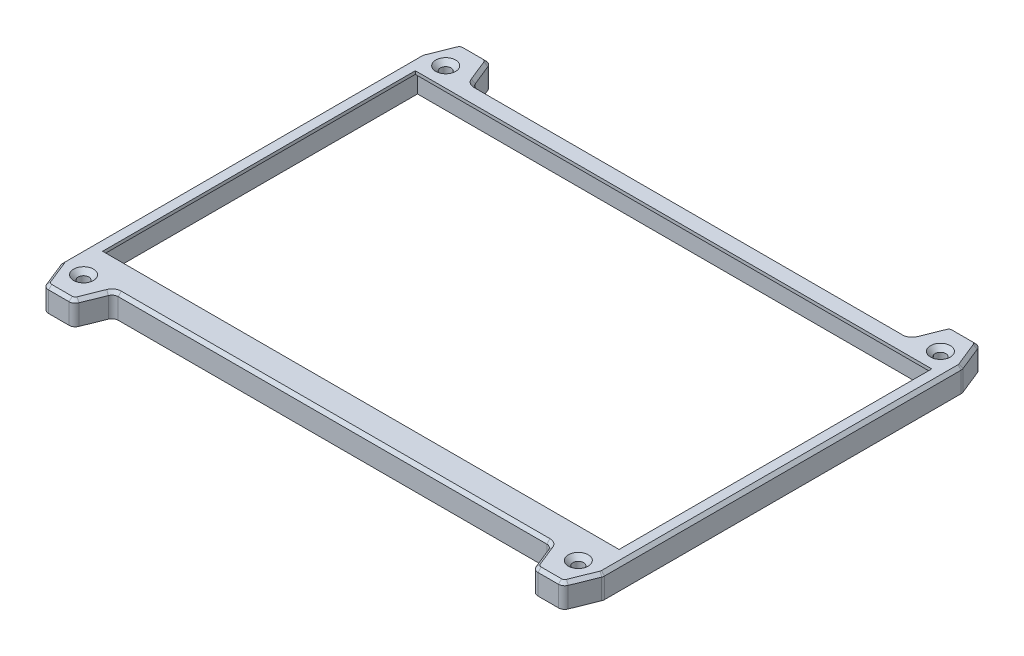
SolidWorks part; units mm, degrees
ref_plane "Front Plane" through (0, 0, 0) normal (0, 0, 1) x (1, 0, 0)
ref_plane "Top Plane" through (0, 0, 0) normal (0, 1, 0) x (1, 0, 0)
ref_plane "Right Plane" through (0, 0, 0) normal (1, 0, 0) x (0, 0, -1)
sketch "Sketch1" plane through (0, 0, 0) normal (0, 1, 0) x (1, 0, 0)
  line L0 (-86, 57) -> (86, 57)
  line L1 (-86, 57) -> (-86, -57)
  line L2 (-86, -57) -> (86, -57)
  line L3 (86, 57) -> (86, -57)
  line L4 (0, -57) -> (0, 57) construction
  line L5 (-86, 0) -> (86, 0) construction
  line L6 (-82.3, -66.2) -> (-73.1, -66.2)
  line L7 (-73.1, -66.2) -> (-69.4, -57)
  line L8 (-69.4, -57) -> (-86, -57)
  line L9 (86, -57) -> (82.3, -66.2)
  line L10 (82.3, -66.2) -> (73.1, -66.2)
  line L11 (73.1, -66.2) -> (69.4, -57)
  line L12 (69.4, -57) -> (86, -57)
  line L13 (-86, 57) -> (-82.3, 66.2)
  line L14 (-82.3, 66.2) -> (-73.1, 66.2)
  line L15 (-73.1, 66.2) -> (-69.4, 57)
  line L16 (-69.4, 57) -> (-86, 57)
  line L17 (86, 57) -> (82.3, 66.2)
  line L18 (82.3, 66.2) -> (73.1, 66.2)
  line L19 (73.1, 66.2) -> (69.4, 57)
  line L20 (69.4, 57) -> (86, 57)
  line L21 (-82.3, -66.2) -> (-86, -57)
  point P0 (0, 0)
  dimension "D1" = 172
  dimension "D2" = 114
  dimension "D3" = 9.2
  dimension "D4" = 9.2
  dimension "D5" = 16.6
extrude "Boss-Extrude1" add sketch "Sketch1" along normal blind 7.5 contours L21 L6 L7 L2 | L3 L0 L1 L2 | L11 L10 L9 L2 | L18 L19 L0 L17 | L15 L14 L13 L0
sketch "Sketch2" plane through (0, 7.5, 0) normal (0, 1, 0) x (1, 0, 0)
  line L0 (-69.4, -57) -> (69.4, -57) construction
  line L1 (-82, 52) -> (82, 52)
  line L2 (-82, 52) -> (-82, -48)
  line L3 (-82, -48) -> (82, -48)
  line L4 (82, 52) -> (82, -48)
  line L5 (-86, 0) -> (-82, 0) construction
  line L9 (-86, 57) -> (-86, -57) construction
  line L10 (82, 2) -> (86, 2) construction
  line L11 (86, 57) -> (86, -57) construction
  dimension "D1" = 100
  dimension "D2" = 164
  dimension "D3" = 9
extrude "Cut-Extrude1" cut sketch "Sketch2" against normal through all
sketch "Sketch8" plane through (0, 0, 0) normal (0, -1, 0) x (1, 0, 0)
  line L0 (-82, 48) -> (-82, 48.75) construction
  line L1 (-82.75, 48.75) -> (82.75, 48.75)
  line L2 (-82.75, 48.75) -> (-82.75, -52.75)
  line L3 (-82.75, -52.75) -> (82.75, -52.75)
  line L4 (82.75, 48.75) -> (82.75, -52.75)
  line L5 (-82, 48) -> (-82.75, 48) construction
  line L6 (82, -52) -> (82, -52.75) construction
  line L7 (82, -52) -> (82.75, -52) construction
  dimension "D1" = 0.75
extrude "Cut-Extrude3" cut sketch "Sketch8" against normal offset from surface (6.5 mm away) 1 up to face at (0, 7.5, -2)
sketch "Sketch3" plane through (0, 7.5, 0) normal (0, 1, 0) x (1, 0, 0)
  line L1 (-78.55, 57.5) -> (78.55, 57.5) construction
  line L2 (-78.55, 57.5) -> (-78.55, -57.5) construction
  line L3 (-78.55, -57.5) -> (78.55, -57.5) construction
  line L4 (78.55, 57.5) -> (78.55, -57.5) construction
  line L5 (0, -57.5) -> (0, 57.5) construction
  line L6 (-78.55, 0) -> (78.55, 0) construction
  point P0 (-78.55, 57.5)
  point P2 (78.55, 57.5)
  point P4 (78.55, -57.5)
  point P6 (-78.55, -57.5)
  point P9 (0, 0)
  dimension "D1" = 115
  dimension "D2" = 157.1
hole_wizard "CSK for M3 Flat Head Machine Screw1" positions "Sketch3" profile "Sketch4" countersink size "M3" standard "ANSI Metric" end condition through all
sketch "Sketch4" plane through (-78.55, 7.5, -57.5) normal (1, 0, 0) x (0, 0, 1)
  line L0 (0, 0) -> (0, 7.5)
  line L1 (0, 7.5) -> (2.2, 7.5)
  line L2 (1.7, 7) -> (1.7, 1.45)
  line L3 (1.7, 1.45) -> (3.15, 0)
  line L5 (3.15, 0) -> (0, 0)
  line L6 (-1.7, 1.45) -> (-3.15, 0) construction
  line L7 (2.2, 7.5) -> (1.7, 7)
  line L8 (-2.2, 7.5) -> (-1.7, 7) construction
  line L11 (0, -6.35) -> (0, 107.95) construction
  dimension "Thru Hole Dia." = 3.4
  dimension "Thru Hole Depth" = 7.5
  dimension "Near C'Sink Dia." = 6.3
  dimension "Near C'Sink Angle" = 90
  dimension "Far C'Sink Dia." = 4.4
  dimension "Far C'Sink Angle" = 90
sketch "Sketch6" plane through (86, 0, 0) normal (1, 0, 0) x (0, 0, -1)
  line L0 (57, 0) -> (-57, 0) construction
  line L1 (50.95, 0) -> (34.7, 0)
  line L2 (50.95, 0) -> (50.95, -2)
  line L3 (50.95, -2) -> (34.7, -2)
  line L4 (34.7, 0) -> (34.7, -2)
  line L5 (57, 7.5) -> (57, 0) construction
  line L6 (26.95, 0) -> (18.95, 0)
  line L7 (26.95, 0) -> (26.95, -2)
  line L8 (26.95, -2) -> (18.95, -2)
  line L9 (18.95, 0) -> (18.95, -2)
  line L10 (12.7, 0) -> (4.7, 0)
  line L11 (12.7, 0) -> (12.7, -2)
  line L12 (12.7, -2) -> (4.7, -2)
  line L13 (4.7, 0) -> (4.7, -2)
  dimension "D1" = 6.05
  dimension "D2" = 16.25
  dimension "D3" = 2
  dimension "D4" = 6.25
  dimension "D5" = 7.75
  dimension "D6" = 2
  dimension "D7" = 8
extrude "Boss-Extrude2" add sketch "Sketch6" against normal blind 1.2 from offset 2 separate body offset against normal yes
sketch "Sketch7" plane through (0, 0, 0) normal (0, -1, 0) x (1, 0, 0)
  line L1 (82, 48) -> (52, 48)
  line L2 (82, 48) -> (82, 53)
  line L3 (82, 53) -> (52, 53)
  line L4 (52, 48) -> (52, 53)
  dimension "D1" = 30
  dimension "D2" = 5
extrude "Cut-Extrude2" cut sketch "Sketch7" against normal blind 7
sketch "Sketch9" plane through (0, 0, -52) normal (0, 0, 1) x (1, 0, 0)
  line L1 (-82, 7.5) -> (82, 7.5)
  line L2 (-82, 7.5) -> (-82, 6.5)
  line L3 (-82, 6.5) -> (82, 6.5)
  line L4 (82, 7.5) -> (82, 6.5)
extrude "Boss-Extrude3" add sketch "Sketch9" along normal blind 0.7
fillet "Fillet1" radius 2 17 edges at (-86, 3.75, 57) (-73.1, 3.75, -66.2) (-69.4, 3.75, -57) (69.4, 3.75, -57) (73.1, 3.75, -66.2) (82.3, 3.75, -66.2) (86, 3.75, -57) (86, 3.75, 57) (82.3, 3.75, 66.2) (73.1, 3.75, 66.2) (69.4, 3.75, 57) (-69.4, 3.75, 57) (-73.1, 3.75, 66.2) (-82.3, 3.75, 66.2) (-86, 3.75, -57) (-82.3, 3.75, -66.2) (52, 6.75, 48)
chamfer "Chamfer1" distance 1 angle 45 33 edges at (86, 7.5, 0) (85.9636, 7.5, -56.9929) (85.9636, 7.5, 56.9929) (84.3299, 7.5, -61.1527) (84.3299, 7.5, 61.1527) (82.0684, 7.5, -65.8572) (82.0684, 7.5, 65.8572) (77.7, 7.5, -66.2) (77.7, 7.5, 66.2) (73.3316, 7.5, -65.8572) (73.3316, 7.5, 65.8572) (71.25, 7.5, -61.6) (71.25, 7.5, 61.6) (69.1684, 7.5, -57.3428) (69.1684, 7.5, 57.3428) (0, 7.5, -57) (0, 7.5, 57) (-69.1684, 7.5, -57.3428) (-69.1684, 7.5, 57.3428) (-71.25, 7.5, -61.6) (-71.25, 7.5, 61.6) (-73.3316, 7.5, -65.8572) (-73.3316, 7.5, 65.8572) (-77.7, 7.5, -66.2) (-77.7, 7.5, 66.2) (-82.0684, 7.5, -65.8572) (-82.0684, 7.5, 65.8572) (-84.3299, 7.5, -61.1527) (-84.3299, 7.5, 61.1527) (-85.9636, 7.5, -56.9929) (-85.9636, 7.5, 56.9929) (-86, 7.5, 0) (67, 7, 53)
